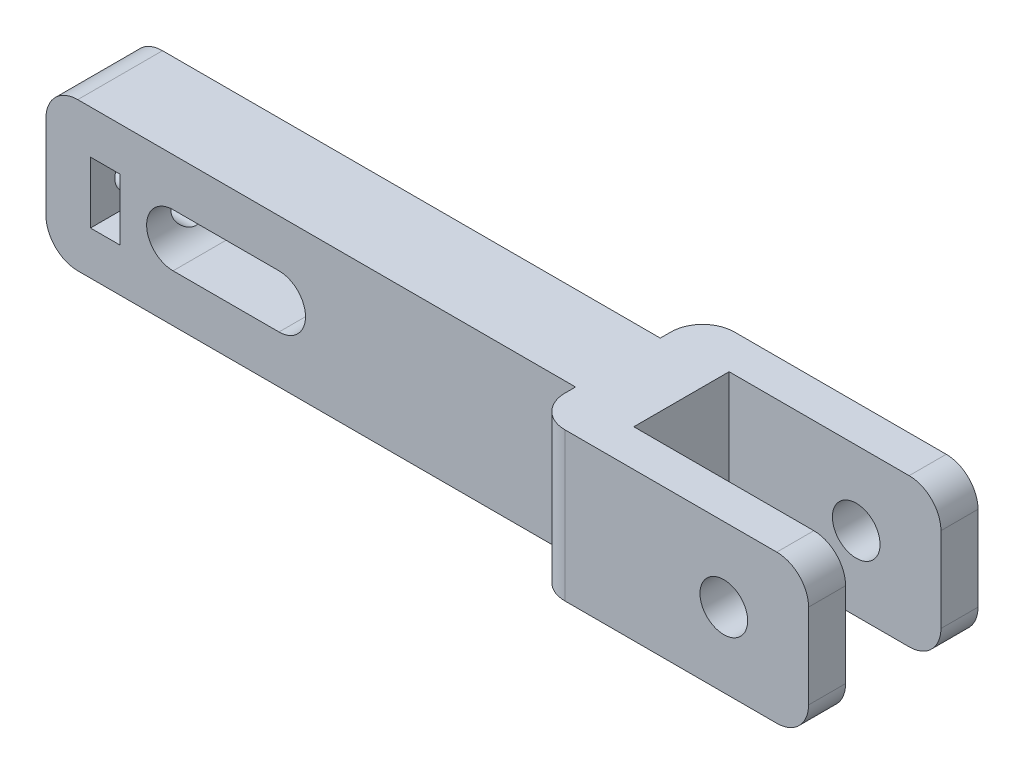
SolidWorks part; units mm, degrees
ref_plane "Front Plane" through (0, 0, 0) normal (0, 0, 1) x (1, 0, 0)
ref_plane "Top Plane" through (0, 0, 0) normal (0, 1, 0) x (1, 0, 0)
ref_plane "Right Plane" through (0, 0, 0) normal (1, 0, 0) x (0, 0, -1)
sketch "Sketch1" plane through (0, 0, 0) normal (0, 1, 0) x (1, 0, 0)
  line L0 (0, -4) -> (0, 4)
  line L1 (76, 8) -> (50, 8)
  line L2 (50, 8) -> (50, -4)
  line L3 (50, -4) -> (0, -4)
  line L4 (76, 8) -> (76, 4.5)
  line L5 (76, 4.5) -> (56, 4.5)
  line L6 (56, 4.5) -> (56, -4.5)
  line L7 (56, -4.5) -> (76, -4.5)
  line L8 (76, -4.5) -> (76, -8)
  line L9 (0, 0) -> (56, 0) construction
  line L12 (76, -8) -> (50, -8)
  line L13 (50, -8) -> (50, 4)
  line L14 (50, 4) -> (0, 4)
  point P2 (0, 0)
  dimension "D1" = 50
  dimension "D2" = 8
  dimension "D3" = 9
  dimension "D4" = 3.5
  dimension "D5" = 20
  dimension "D6" = 26
  dimension "D7" = 16
extrude "Boss-Extrude1" add sketch "Sketch1" along normal mid plane 14 contours L2 L9 L6 L5 L4 L1 | L9 L13 L12 L8 L7 L6 | L0 L9 L2 L14 | L9 L0 L3 L13
hole_wizard "M4 Clearance Hole1" positions "Sketch3" profile "Sketch4" hole size "M4" standard "ANSI Metric" end condition through all
sketch "Sketch3" plane through (0, 0, -8) normal (0, 0, -1) x (-1, 0, 0)
  line L0 (-68, 0) -> (-76, 0) construction
  line L2 (-76, 7) -> (-76, -7) construction
  point P0 (-68, 0)
  dimension "D1" = 8
sketch "Sketch4" plane through (68, 0, -8) normal (1, 0, 0) x (0, 1, 0)
  line L0 (0, 0) -> (0, 16)
  line L1 (0, 16) -> (2.25, 16)
  line L2 (2.25, 16) -> (2.25, 0)
  line L5 (2.25, 0) -> (0, 0)
  line L11 (0, -6.35) -> (0, 107.95) construction
  dimension "Thru Hole Dia." = 4.5
  dimension "Thru Hole Depth" = 16
sketch "Sketch6" plane through (0, 0, -4) normal (0, 0, -1) x (-1, 0, 0)
  line L0 (-12, 0) -> (-22, 0) construction
  line L1 (-12, -2.5) -> (-22, -2.5)
  line L2 (-12, 2.5) -> (-22, 2.5)
  line L3 (-12, 0) -> (0, 0) construction
  line L4 (-76, 7) -> (-76, -7) construction
  arc A0 (-12, -2.5) -> (-12, 2.5) centre (-12, 0) ccw
  arc A1 (-22, 2.5) -> (-22, -2.5) centre (-22, 0) ccw
  point P3 (-17, 0)
  dimension "D1" = 2.5
  dimension "D2" = 10
  dimension "D3" = 54
extrude "Cut-Extrude1" cut sketch "Sketch6" against normal through all both and the other way through all
ref_plane "Plane1" through (7, 0, 0) normal (-1, 0, 0) x (0, 0, 1)
sketch "Sketch7" plane through (7, 0, 0) normal (-1, 0, 0) x (0, 0, 1)
  line L1 (0, 0) -> (-0.25, 0) construction
  line L2 (4, 2.9) -> (-1.9243, 2.9)
  line L3 (-1.9243, 2.9) -> (-3.5986, 0)
  line L4 (-3.5986, 0) -> (-1.9243, -2.9)
  line L5 (-1.9243, -2.9) -> (4, -2.9)
  line L7 (4, 7) -> (4, -7) construction
  line L8 (4, 2.9) -> (4, -2.9)
  line L11 (2.4001, -1.2098) -> (3.2373, 0.2402) [skipped]
  line L12 (2.4001, 1.2098) -> (1.563, 2.6598) [skipped]
  dimension "D1" = 5.8
  dimension "D3" = 0.25
extrude "Cut-Extrude2" cut sketch "Sketch7" along normal blind 2.8
hole_wizard "M3 Clearance Hole1" positions "3DSketch3" profile "Sketch10" hole size "M3" standard "ANSI Metric"
sketch3d "3DSketch3"
  point P0 (0, 0, 0)
sketch "Sketch10" plane through (0, 0, 0) normal (0, 1, 0) x (0, 0, 1)
  line L0 (0, 0) -> (0, 17.0215)
  line L1 (0, 17.0215) -> (1.7, 16)
  line L2 (1.7, 16) -> (1.7, 0)
  line L5 (1.7, 0) -> (0, 0)
  line L10 (0, 17.0215) -> (-1.7, 16) construction
  line L11 (0, -6.35) -> (0, 107.95) construction
  dimension "Hole Dia." = 3.4
  dimension "Hole Depth" = 16
  dimension "Drill Angle" = 118
fillet "Fillet1" radius 3 8 edges at (50, 0, 8) (50, 0, -8) (0, -7, 0) (0, 7, 0) (76, -7, 6.25) (76, 7, 6.25) (76, -7, -6.25) (76, 7, -6.25)
